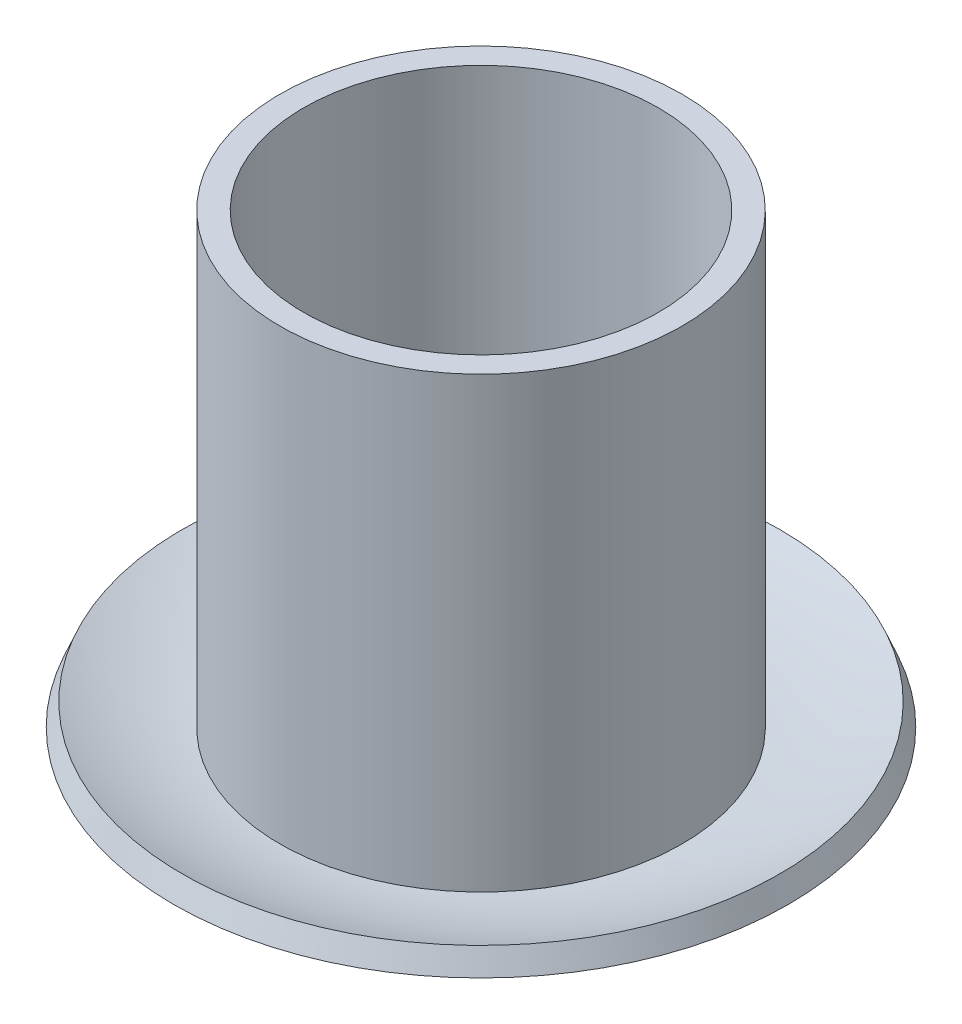
SolidWorks part; units mm, degrees
ref_plane "Front Plane" through (0, 0, 0) normal (0, 0, 1) x (1, 0, 0)
ref_plane "Top Plane" through (0, 0, 0) normal (0, 1, 0) x (1, 0, 0)
ref_plane "Right Plane" through (0, 0, 0) normal (1, 0, 0) x (0, 0, -1)
sketch "Sketch1" plane through (0, 0, 0) normal (0, 0, 1) x (1, 0, 0)
  line L0 (1.7, 4) -> (1.5, 4)
  line L1 (1.5, 4) -> (1.5, 0)
  line L3 (2.6, 0.2147) -> (2.5248, 0.4)
  line L5 (1.7, 0.2073) -> (1.7, 4)
  line L6 (0, 0) -> (1.5, 0) construction
  line L7 (2.5248, 0.4) -> (2.6, 0.2147) construction
  line L8 (2.5248, 0.4) -> (2.7101, 0.4752) construction
  line L9 (2.6, 0.2147) -> (2.7853, 0.2899) construction
  line L10 (2.7101, 0.4752) -> (2.7853, 0.2899) construction
  line L11 (0, 0) -> (0, 4) construction
  arc A0 (1.7, 0.2073) -> (2.5248, 0.4) centre (1.5, 2.9255) ccw
  arc A1 (1.5, 0) -> (2.6, 0.2147) centre (1.5, 2.9255) ccw
  dimension "D1" = 0.2
  dimension "D2" = 4
  dimension "D3" = 1.7
  dimension "D4" = 2.6
  dimension "D5" = 0.4
revolve "Revolve1" add sketch "Sketch1" angle 360 about L11
